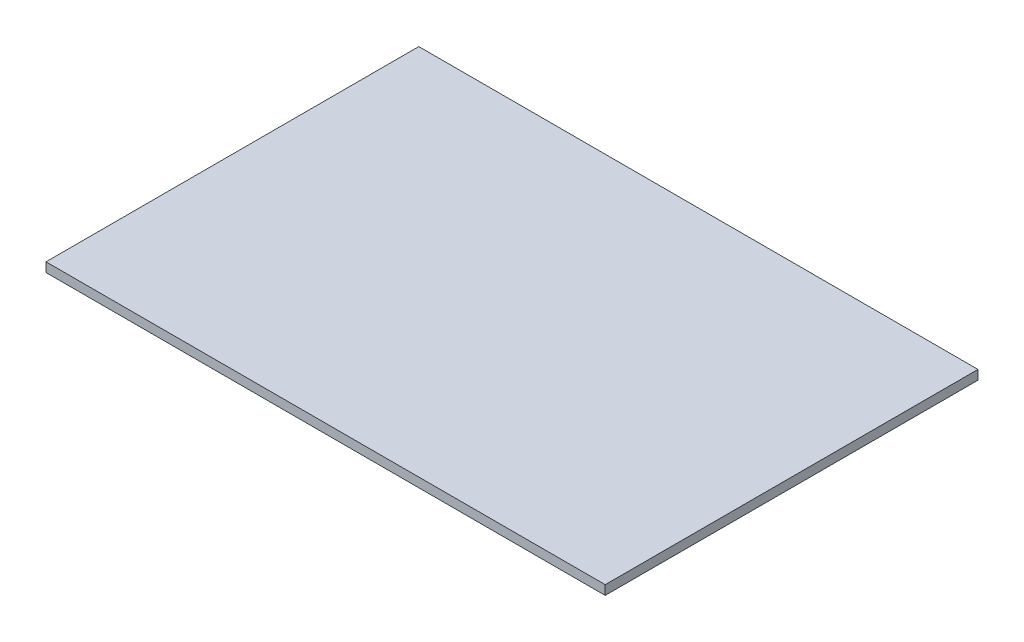
SolidWorks part; units mm, degrees
ref_plane "Front Plane" through (0, 0, 0) normal (0, 0, 1) x (1, 0, 0)
ref_plane "Top Plane" through (0, 0, 0) normal (0, 1, 0) x (1, 0, 0)
ref_plane "Right Plane" through (0, 0, 0) normal (1, 0, 0) x (0, 0, -1)
sketch "Sketch1" plane through (0, 0, 0) normal (0, 1, 0) x (1, 0, 0)
  line L1 (-190.5, 127) -> (190.5, 127)
  line L2 (-190.5, 127) -> (-190.5, -127)
  line L3 (-190.5, -127) -> (190.5, -127)
  line L4 (190.5, 127) -> (190.5, -127)
  line L5 (-190.5, 127) -> (190.5, -127) construction
  line L6 (-190.5, -127) -> (190.5, 127) construction
  point P0 (0, 0)
  dimension "D1" = 381
  dimension "D2" = 254
extrude "Boss-Extrude1" add sketch "Sketch1" along normal blind 6.35
